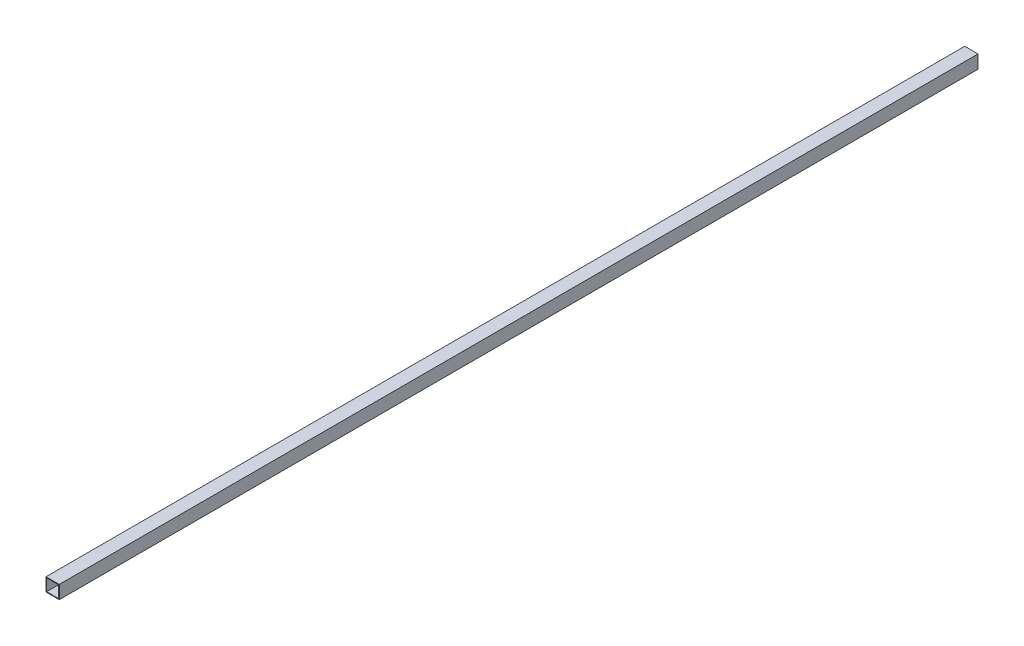
SolidWorks part; units mm, degrees
ref_plane "Front Plane" through (0, 0, 0) normal (0, 0, 1) x (1, 0, 0)
ref_plane "Top Plane" through (0, 0, 0) normal (0, 1, 0) x (1, 0, 0)
ref_plane "Right Plane" through (0, 0, 0) normal (1, 0, 0) x (0, 0, -1)
sketch "Sketch1" plane through (0, 0, 0) normal (0, 0, 1) x (1, 0, 0)
  line L5 (-15.875, 15.875) -> (15.875, 15.875)
  line L6 (-15.875, 15.875) -> (-15.875, -15.875)
  line L11 (-15.875, -15.875) -> (15.875, -15.875)
  line L12 (15.875, 15.875) -> (15.875, -15.875)
  line L13 (-15.875, 15.875) -> (15.875, -15.875) construction
  line L14 (-15.875, -15.875) -> (15.875, 15.875) construction
  line L15 (-14.2875, 14.2875) -> (14.2875, 14.2875)
  line L16 (-14.2875, 14.2875) -> (-14.2875, -14.2875)
  line L17 (-14.2875, -14.2875) -> (14.2875, -14.2875)
  line L18 (14.2875, 14.2875) -> (14.2875, -14.2875)
  line L19 (-14.2875, 14.2875) -> (14.2875, -14.2875) construction
  line L20 (-14.2875, -14.2875) -> (14.2875, 14.2875) construction
  point P0 (0, 0)
  point P6 (0, 0)
  dimension "D1" = 31.75
  dimension "D2" = 31.75
  dimension "D3" = 1.5875
extrude "Boss-Extrude1" add sketch "Sketch1" along normal blind 2200
